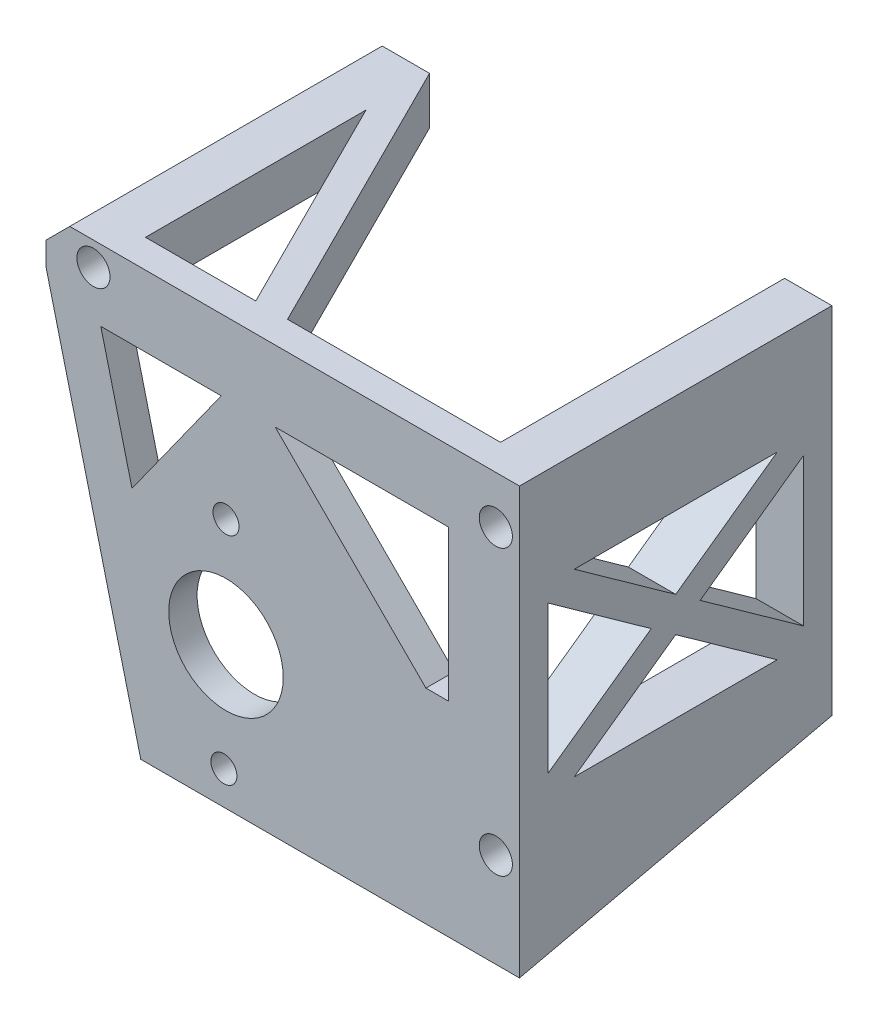
SolidWorks part; units mm, degrees
ref_plane "正面" through (0, 0, 0) normal (0, 0, 1) x (1, 0, 0)
ref_plane "平面" through (0, 0, 0) normal (0, 1, 0) x (1, 0, 0)
ref_plane "右側面" through (0, 0, 0) normal (1, 0, 0) x (0, 0, -1)
sketch "Sketch1" plane through (0, 0, 0) normal (0, 0, 1) x (1, 0, 0)
  line L1 (-50, 45) -> (50, 45)
  line L2 (-50, 45) -> (-50, -45)
  line L3 (-50, -45) -> (50, -45)
  line L4 (50, 45) -> (50, -45)
  line L5 (-50, 45) -> (50, -45) construction
  line L6 (-50, -45) -> (50, 45) construction
  point P0 (0, 0)
  dimension "D1" = 90
  dimension "D2" = 100
extrude "Boss-Extrude1" add sketch "Sketch1" along normal blind 6
sketch "Sketch2" plane through (0, 0, 6) normal (0, 0, 1) x (1, 0, 0)
  line L0 (-50, -15) -> (50, -15) construction
  line L1 (-50, 45) -> (-50, -45) construction
  line L2 (50, -45) -> (50, 45) construction
  line L3 (-50, -45) -> (50, -45) construction
  circle A0 centre (-12, -15) radius 12.1
  dimension "D3" = 24.2
  dimension "D1" = 38
  dimension "D2" = 30
extrude "Cut-Extrude1" cut sketch "Sketch2" against normal up to next
sketch "Sketch3" plane through (0, 0, 0) normal (0, 0, -1) x (-1, 0, 0)
  line L0 (50, -45) -> (-50, -45) construction
  line L1 (-50, -45) -> (-40, -45)
  line L2 (-50, -45) -> (-50, 45)
  line L3 (-50, 45) -> (-40, 45)
  line L4 (-40, -45) -> (-40, 45)
  dimension "D1" = 90
  dimension "D2" = 10
extrude "Boss-Extrude2" add sketch "Sketch3" along normal blind 60
sketch "Sketch5" plane through (0, 0, 0) normal (0, 0, -1) x (-1, 0, 0)
  line L0 (-40, 45) -> (50, 45) construction
  line L1 (50, 45) -> (50, -45) construction
  line L2 (45, 45) -> (35, 45)
  line L3 (45, 45) -> (45, 35)
  line L4 (45, 35) -> (35, 35)
  line L5 (35, 45) -> (35, 35)
  dimension "D1" = 5
  dimension "D2" = 10
  dimension "D3" = 10
extrude "Boss-Extrude4" add sketch "Sketch5" along normal blind 60
sketch "Sketch6" plane through (0, 0, 6) normal (0, 0, 1) x (1, 0, 0)
  circle A0 centre (-12, -15) radius 48 construction
  dimension "D1" = 96
sketch "Sketch7" plane through (0, 0, 6) normal (0, 0, 1) x (1, 0, 0)
  line L0 (45, 45) -> (45, -45) construction
  line L1 (50, 45) -> (-50, 45) construction
  line L2 (-50, -45) -> (50, -45) construction
  line L3 (50, -45) -> (50, 45) construction
  circle A0 centre (45, 35) radius 3.5
  circle A1 centre (45, -25) radius 3.5
  dimension "D2" = 7
  dimension "D3" = 7
  dimension "D1" = 5
  dimension "D4" = 10
  dimension "D5" = 20
extrude "Cut-Extrude2" cut sketch "Sketch7" against normal blind 35
sketch "Sketch8" plane through (0, 0, -29) normal (0, 0, 1) x (1, 0, 0)
  circle A0 centre (45, 35) radius 1.6
  circle A1 centre (45, -25) radius 1.6
  dimension "D1" = 3.2
  dimension "D2" = 3.2
extrude "Cut-Extrude3" cut sketch "Sketch8" against normal up to next
sketch "Sketch9" plane through (0, 0, -60) normal (0, 0, -1) x (-1, 0, 0)
  line L0 (40, 45) -> (40, 35) construction
  line L1 (45, 45) -> (35, 45) construction
  line L2 (35, 35) -> (45, 35) construction
  circle A0 centre (40, 40) radius 1.6
  dimension "D1" = 3.2
extrude "Cut-Extrude4" cut sketch "Sketch9" against normal up to next
sketch "Sketch10" plane through (0, 0, 6) normal (0, 0, 1) x (1, 0, 0)
  circle A0 centre (-40, 40) radius 3.5
  dimension "D1" = 7
extrude "Cut-Extrude5" cut sketch "Sketch10" against normal blind 35
hole_wizard "M5 Clearance Hole2" positions "Sketch14" profile "Sketch15" hole size "M5" standard "ISO" end condition up to next
sketch "Sketch14" plane through (0, 0, 6) normal (0, 0, 1) x (1, 0, 0)
  point P0 (-11.9924, 7.9322)
  point P2 (-12.4375, -37.928)
sketch "Sketch15" plane through (-11.9924, 7.9322, 6) normal (1, 0, 0) x (0, -1, 0)
  line L0 (0, 0) -> (0, 6)
  line L1 (0, 6) -> (2.75, 6)
  line L2 (2.75, 6) -> (2.75, 0)
  line L5 (2.75, 0) -> (0, 0)
  line L11 (0, -6.35) -> (0, 107.95) construction
  dimension "Thru Hole Dia." = 5.5
  dimension "Thru Hole Depth" = 6
sketch "Sketch16" plane through (50, 0, 0) normal (1, 0, 0) x (0, 0, -1)
  line L0 (-6, -45) -> (-6, 45) construction
  line L1 (60, 45) -> (60, -45) construction
  line L2 (-6, 25) -> (60, 25) construction
  line L3 (-6, 25) -> (-6, -15) construction
  line L4 (-6, -15) -> (60, -15) construction
  line L5 (60, 25) -> (60, -15) construction
  line L6 (-6, 45) -> (60, 45) construction
  line L7 (-6, -45) -> (60, -45) construction
  line L8 (-1, 25) -> (55, -15) construction
  line L9 (-1, 25) -> (55, 25) construction
  line L10 (-1, 25) -> (-1, -15) construction
  line L11 (-1, -15) -> (55, -15) construction
  line L12 (55, 25) -> (55, -15) construction
  line L13 (55, 25) -> (-1, -15) construction
  line L14 (0, 20.599) -> (0, -10.599)
  line L15 (0, -10.599) -> (21.8386, 5)
  line L16 (21.8386, 5) -> (0, 20.599)
  line L17 (27, 25) -> (27, -15) construction
  line L18 (54, -10.599) -> (32.1614, 5)
  line L19 (54, 20.599) -> (54, -10.599)
  line L20 (32.1614, 5) -> (54, 20.599)
  line L21 (27, 1.3133) -> (5.5614, -14)
  line L22 (27, 1.3133) -> (48.4386, -14)
  line L23 (48.4386, -14) -> (5.5614, -14)
  line L24 (-1, 5) -> (55, 5) construction
  line L25 (27, 8.6867) -> (48.4386, 24)
  line L26 (27, 8.6867) -> (5.5614, 24)
  line L27 (48.4386, 24) -> (5.5614, 24)
  dimension "D1" = 20
  dimension "D2" = 30
  dimension "D3" = 5
  dimension "D4" = 5
  dimension "D5" = 3
  dimension "D6" = 3
  dimension "D7" = 1
  dimension "D8" = 3
  dimension "D9" = 1
extrude "Cut-Extrude7" cut sketch "Sketch16" against normal up to next
sketch "Sketch17" plane through (0, 0, 6) normal (0, 0, 1) x (1, 0, 0)
  line L0 (-50, 35) -> (-30, -45)
  line L1 (-50, 45) -> (-50, -45) construction
  line L2 (-50, -45) -> (50, -45) construction
  dimension "D1" = 20
  dimension "D2" = 80
extrude "Cut-Extrude8" cut sketch "Sketch17" against normal blind 35 and the other way through all flip side to cut
chamfer "Chamfer1" distance 5 angle 45 1 edges at (-50, 45, 3)
sketch "Sketch18" plane through (0, 0, 6) normal (0, 0, 1) x (1, 0, 0)
  line L0 (-38.4422, 30) -> (-31.8515, 3.6369)
  line L1 (-31.8515, 3.6369) -> (-13.0023, 30)
  line L2 (-13.0023, 30) -> (-38.4422, 30)
  line L3 (50, 45) -> (-45, 45) construction
  line L4 (-50, 35) -> (-30, -45) construction
  line L5 (-48.75, 30) -> (50, 30) construction
  line L6 (50, -45) -> (50, 45) construction
  line L7 (-1.6065, 30) -> (30.2389, -1.8455)
  line L8 (30.2389, -1.8455) -> (35, -1.8455)
  line L9 (35, -1.8455) -> (35, 30)
  line L10 (-1.6065, 30) -> (35, 30)
  dimension "D1" = 15
  dimension "D2" = 10
  dimension "D3" = 15
extrude "Cut-Extrude9" cut sketch "Sketch18" against normal blind 35
sketch "Sketch19" plane through (50, 0, 0) normal (1, 0, 0) x (0, 0, -1)
  line L0 (60, -30) -> (-6, -45)
  line L1 (60, 45) -> (60, -45) construction
  line L2 (-6, -45) -> (60, -45)
  line L3 (60, -45) -> (60, -30)
  dimension "D1" = 15
extrude "Cut-Extrude10" cut sketch "Sketch19" against normal up to next
sketch "Sketch20" plane through (0, 45, 0) normal (0, 1, 0) x (1, 0, 0)
  line L0 (-35, 60) -> (-5, 0)
  line L1 (40, 0) -> (-35, 0) construction
  line L2 (-5, 0) -> (-35, 0)
  line L3 (-35, 0) -> (-35, 60)
  line L4 (-35, 46.5836) -> (-11.7082, 0)
  line M11 (40, 0) -> (-35, 0)
  dimension "D1" = 30
  dimension "D2" = 6
extrude "Boss-Extrude5" add sketch "Sketch20" against normal blind 10 contours L3 L4 L0 M11
